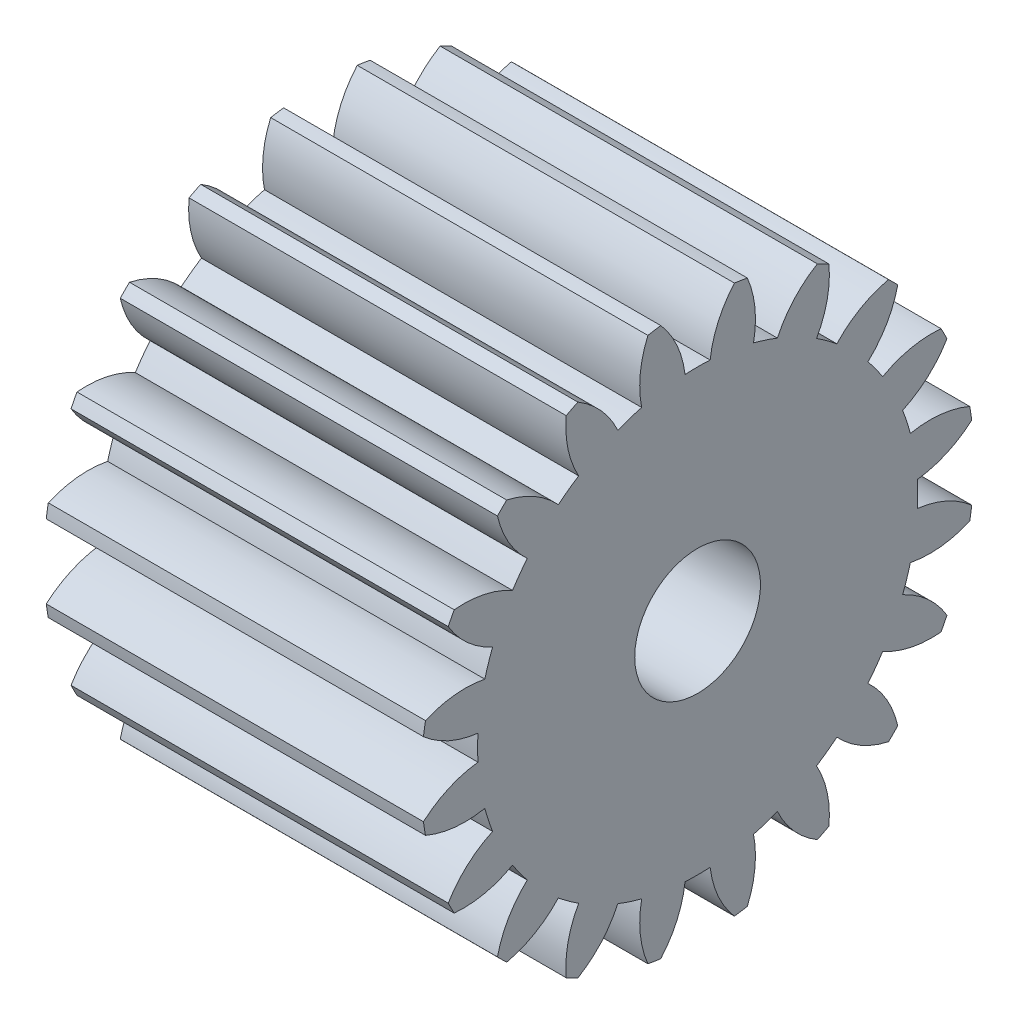
SolidWorks part; units mm, degrees
ref_plane "Plane1" through (0, 0, 0) normal (0, 0, 1) x (1, 0, 0)
ref_plane "Plane2" through (0, 0, 0) normal (0, 1, 0) x (1, 0, 0)
ref_plane "Plane3" through (0, 0, 0) normal (1, 0, 0) x (0, 0, -1)
other "Configuration Table"
sketch "HoldingSke" plane through (0, 0, 0) normal (0, 1, 0) x (1, 0, 0)
  line L0 (0, 0) -> (1.1746, -0.4275)
  line L1 (-15, 0) -> (100, 0) construction
  line L2 (0, 0) -> (-2.1039, 2.3779)
  line L3 (0, 0) -> (-11.863, 4.5341)
  line L4 (0, 0) -> (8.1152, 2.9537)
  line L5 (0, 0) -> (-46.8476, -17.4728)
  line L6 (0, 0) -> (-9.9476, -6.7116)
  line L7 (-2.1039, 2.3779) -> (8.6586, 51.2059)
  line L8 (-76.2, 54.61) -> (-75.5, 54.61)
  line L9 (-71.009, 38.7566) -> (-53.1078, 45.2721)
  line L10 (-76.2, 71.12) -> (104.1128, 71.12)
  line L11 (0, 0) -> (-12, 0)
  line L12 (-76.2, 101.6) -> (-76.17, 101.6)
  line L13 (24.9733, 27.94) -> (52.9518, 28.4284)
  line L14 (24.9733, 27.94) -> (24.9743, 27.94)
  line L15 (24.9733, 27.94) -> (100.4006, 29.5858)
  line L16 (-63.627, -0.8) -> (-12.827, -0.8)
  circle A0 centre (0, 0) radius 2
  circle A1 centre (0, 0) radius 6.999
  circle A2 centre (0, 0) radius 37.5
  circle A3 centre (0, 0) radius 2
  dimension "MHD" = 13.998
  dimension "Hub_dia" = 75
  dimension "Bore" = 4
  dimension "MBD" = 4
  dimension "Num_teeth" = 20
  dimension "Pitch" = 1.25
  dimension "Overall_len" = 50
  dimension "Show_teeth" = 20
  dimension "Thickness" = 12
  dimension "OAL" = 50.0001
  dimension "T_dim" = 0.7
  dimension "Ap" = 20
  dimension "H" = 19.05
  dimension "Pitch_radius" = 180.3128
  dimension "Width" = 12
  dimension "Backlash" = 0.03
  dimension "Addendum_fac" = 1
  dimension "Dedendum_fac" = 1.25
  dimension "Clearance_fac" = 0.25
  dimension "Dedendum_add" = 0.001
  dimension "Module" = 0.8
sketch "BasProSke" plane through (0, 0, 0) normal (0, 1, 0) x (1, 0, 0)
  line L0 (-10, 0) -> (60, 0) construction
  line L1 (0, 0) -> (0, 8.8)
  line L2 (0, 0) -> (12, 0)
  line L3 (12, 0) -> (12, 8.8)
  line L4 (12, 8.8) -> (0, 8.8)
  dimension "Thickness" = 12
  dimension "Diameter" = 17.6
revolve "Base-Revolve" add sketch "BasProSke" angle 360 about L0
sketch "TooCutSke" plane through (0, 0, 0) normal (1, 0, 0) x (0, 0, -1)
  line L1 (0, 0) -> (0, 107) construction
  line L2 (0, 0) -> (-0.6801, 7.971) construction
  line L3 (0, 0) -> (-2.4965, 15.7621) construction
  line L4 (-0.6801, 7.971) -> (-1.2482, 7.8811) construction
  arc A0 (0.3993, 6.9876) -> (-0.3993, 6.9876) centre (0, 0) ccw
  arc A1 (1.1915, 8.7446) -> (-1.1915, 8.7446) centre (0, 0) ccw
  circle A2 centre (0, 0) radius 8 construction
  circle A3 centre (0, 0) radius 7.5175 construction
  arc A4 (-0.3993, 6.9876) -> (-1.1915, 8.7446) centre (-3.5772, 6.6119) ccw
  arc A5 (1.1915, 8.7446) -> (0.3993, 6.9876) centre (3.5772, 6.6119) ccw
  dimension "Root_dia" = 13.998
  dimension "Overcut_dia" = 17.6508
  dimension "Pitch_dia" = 16
  dimension "Base_dia" = 15.0351
  dimension "Flank_rad" = 3.2
  dimension "Half_ang" = 9
  dimension "Half_CT" = 0.5752
extrude "ToothCut" cut sketch "TooCutSke" along normal through all
fillet "Breaks" [suppressed] radius 0.016
fillet "RootFillets" [suppressed] radius 0.201
pattern_circular "TeethCuts" count 20 every 18 about axis through (-10, 0, 0) along (1, 0, 0) of "ToothCut", "RootFillets", "Breaks"
sketch "HubNeaOneSke" plane through (0, 0, 0) normal (-1, 0, 0) x (0, 0, 1)
  circle A0 centre (0, 0) radius 6.999
  dimension "Diameter" = 13.998
extrude "HubNearOne" [suppressed] add sketch "HubNeaOneSke" along normal blind 38.0001
sketch "HubNeaBotSke" plane through (0, 0, 0) normal (-1, 0, 0) x (0, 0, 1)
  circle A0 centre (0, 0) radius 6.999
  dimension "Diameter" = 13.998
extrude "HubNearBoth" [suppressed] add sketch "HubNeaBotSke" along normal blind 19
ref_plane "FarPln" through (12, 0, 0) normal (1, 0, 0) x (0, 0, -1)
sketch "HubFarSke" plane through (12, 0, 0) normal (1, 0, 0) x (0, 0, -1)
  circle A0 centre (0, 0) radius 6.999
  dimension "Diameter" = 13.998
extrude "HubFar" [suppressed] add sketch "HubFarSke" along normal blind 19
sketch "BorSke" plane through (0, 0, 0) normal (1, 0, 0) x (0, 0, -1)
  circle A0 centre (0, 0) radius 2
  dimension "Diameter" = 4
extrude "Bore" cut sketch "BorSke" along normal mid plane 100.0001
sketch "KeySke" plane through (0, 0, 0) normal (1, 0, 0) x (0, 0, -1)
  line L0 (-0.8, 0) -> (-0.8, 2.7)
  line L1 (-0.8, 2.7) -> (0.8, 2.7)
  line L2 (0.8, 2.7) -> (0.8, 0)
  line L3 (0, 0) -> (0, 34) construction
  line L4 (-0.8, 0) -> (0.8, 0)
  dimension "Offset" = 2.7
  dimension "Width" = 1.6
extrude "Keyway" [suppressed] cut sketch "KeySke" along normal mid plane 100.0001
pattern_circular "Keyway2" [suppressed] count 2 every 90 about axis through (-10, 0, 0) along (1, 0, 0)
equation "' \"Module@HoldingSke\" = 6.35"
equation "' \"Num_teeth@HoldingSke\" = 12"
equation "' \"Ap@HoldingSke\" =  20"
equation "' \"Ap@HoldingSke\" = 20"
equation "' \"Width@HoldingSke\" = 0.5 * 25.4"
equation "' \"Hub_dia@HoldingSke\"= 1 * 25.4"
equation "' \"Hub_dia@HoldingSke\" = 1 * 25.4"
equation "' \"Overall_len@HoldingSke\" = 1.0 * 25.4"
equation "' \"Bore@HoldingSke\" = 0.75 * 25.4"
equation "' \"T_dim@HoldingSke\" = 0.1 * 25.4"
equation "' \"Width@KeySke\" = 0.25 * 25.4"
equation "' \"Show_teeth@HoldingSke\" = 13"
equation "' \"Backlash@HoldingSke\" = 0.009 * 25.4"
equation "' \"Addendum_fac@HoldingSke\" = 1.0"
equation "' \"Dedendum_fac@HoldingSke\" = 1.25"
equation "' \"Dedendum_add@HoldingSke\" = 0.00005 * 25.4"
equation "' \"Clearance_fac@HoldingSke\" = 0.25"
equation "\"Pitch@HoldingSke\" = 1 / \"Module@HoldingSke\""
equation "\"Overcut_dia@TooCutSke\" = (\"Num_teeth@HoldingSke\" + 2 * \"Addendum_fac@HoldingSke\") / \"Pitch@HoldingSke\" + 0.002 * 25.4"
equation "\"Pitch_dia@TooCutSke\" = \"Num_teeth@HoldingSke\" / \"Pitch@HoldingSke\""
equation "\"Base_dia@TooCutSke\" = \"Num_teeth@HoldingSke\" / \"Pitch@HoldingSke\" * cos((\"Ap@HoldingSke\"  * 3.14159265 / 180))"
equation "\"Root_dia@TooCutSke\" = (\"Num_teeth@HoldingSke\" + 2) / \"Pitch@HoldingSke\" - 2 * (\"Addendum_fac@HoldingSke\" + \"Dedendum_fac@HoldingSke\") / \"Pitch@HoldingSke\" - \"Dedendum_add@HoldingSke\" * 2"
equation "\"Half_ang@TooCutSke\" = 180 / \"Num_teeth@HoldingSke\""
equation "\"Half_CT@TooCutSke\" = \"Num_teeth@HoldingSke\" / \"Pitch@HoldingSke\" * sin((3.14159265 / 2 / \"Num_teeth@HoldingSke\")) / 2 - 7 * \"Backlash@HoldingSke\" / 4"
equation "\"Flank_rad@TooCutSke\" = \"Num_teeth@HoldingSke\" / \"Pitch@HoldingSke\" / 5"
equation "\"Radius@RootFillets\" = \"Clearance_fac@HoldingSke\" / \"Pitch@HoldingSke\" + \"Dedendum_add@HoldingSke\""
equation "\"Break_rad@Breaks\" = 0.02 / \"Pitch@HoldingSke\""
equation "\"Thickness@HoldingSke\" = \"Width@HoldingSke\""
equation "\"OAL@HoldingSke\" = \"Thickness@HoldingSke\""
equation "\"MHD@HoldingSke\" = (\"Num_teeth@HoldingSke\" + 2) / \"Pitch@HoldingSke\" - 2 * (\"Addendum_fac@HoldingSke\" + \"Dedendum_fac@HoldingSke\")  / \"Pitch@HoldingSke\" - \"Dedendum_add@HoldingSke\" * 2"
equation "\"MBD@HoldingSke\" = (\"Num_teeth@HoldingSke\" + 2) / \"Pitch@HoldingSke\" - 2 * (\"Addendum_fac@HoldingSke\" + \"Dedendum_fac@HoldingSke\")  / \"Pitch@HoldingSke\" - \"Dedendum_add@HoldingSke\" * 2 - 0.002 * 25.4"
equation "\"MHD@HoldingSke\" = ((sgn( \"MHD@HoldingSke\" - \"Hub_dia@HoldingSke\" )-1)*( \"MHD@HoldingSke\" - \"Hub_dia@HoldingSke\" ))/-2+ \"Hub_dia@HoldingSke\""
equation "\"MBD@HoldingSke\" = ((sgn( \"MBD@HoldingSke\" - \"Bore@HoldingSke\" )-1)*( \"MBD@HoldingSke\" - \"Bore@HoldingSke\" ))/-2+ \"Bore@HoldingSke\""
equation "\"OAL@HoldingSke\" = ((sgn( \"OAL@HoldingSke\" - \"Overall_len@HoldingSke\" )+1)*( \"OAL@HoldingSke\" - \"Overall_len@HoldingSke\" ))/2 + \"Overall_len@HoldingSke\" + 0.000002 * 25.4"
equation "\"Num_teeth@TeethCuts\" = int( \"Show_teeth@HoldingSke\" ) + 1"
equation "\"Num_teeth@TeethCuts\" = ((sgn( \"Num_teeth@TeethCuts\" - \"Num_teeth@HoldingSke\" )-1)*( \"Num_teeth@TeethCuts\" - \"Num_teeth@HoldingSke\" ))/-2+ \"Num_teeth@HoldingSke\""
equation "\"Num_teeth@TeethCuts\" = ((sgn( \"Num_teeth@TeethCuts\" - 2.0)+1)*( \"Num_teeth@TeethCuts\" - 2.0))/2 +2.0"
equation "\"Angle@TeethCuts\" = 360.0 / \"Num_teeth@HoldingSke\""
equation "\"Diameter@BasProSke\" = (\"Num_teeth@HoldingSke\" + 2 * \"Addendum_fac@HoldingSke\") / \"Pitch@HoldingSke\""
equation "\"Thickness@BasProSke\"  = \"Thickness@HoldingSke\""
equation "' \"Fillet_rad@BasProSke\" =  \"Thickness@HoldingSke\" * 0.05"
equation "' \"Fillet_rad@BasProSke\" = \"Thickness@HoldingSke\" * 0.05"
equation "\"MHD@HoldingSke\" = ((sgn( \"MHD@HoldingSke\" - \"Root_dia@TooCutSke\" )-1)*( \"MHD@HoldingSke\" - \"Root_dia@TooCutSke\" ))/-2+ \"Root_dia@TooCutSke\""
equation "\"Diameter@HubNeaOneSke\" = \"MHD@HoldingSke\""
equation "\"Length@HubNearOne\" = \"OAL@HoldingSke\" - \"Thickness@BasProSke\""
equation "\"Diameter@HubNeaBotSke\" = \"MHD@HoldingSke\""
equation "\"Length@HubNearBoth\" = ( \"OAL@HoldingSke\" - \"Thickness@BasProSke\" ) / 2.0"
equation "\"Thickness@FarPln\" = \"Thickness@BasProSke\""
equation "\"Diameter@HubFarSke\" = \"MHD@HoldingSke\""
equation "\"Length@HubFar\" = ( \"OAL@HoldingSke\" - \"Thickness@BasProSke\" ) / 2.0"
equation "\"Diameter@BorSke\" = \"MBD@HoldingSke\""
equation "\"D1@Bore\" = \"OAL@HoldingSke\" * 2.0"
equation "\"D1@Keyway\" = \"OAL@HoldingSke\" * 2.0"
equation "\"Offset@KeySke\" = \"T_dim@HoldingSke\" + \"MBD@HoldingSke\" / 2.0"
